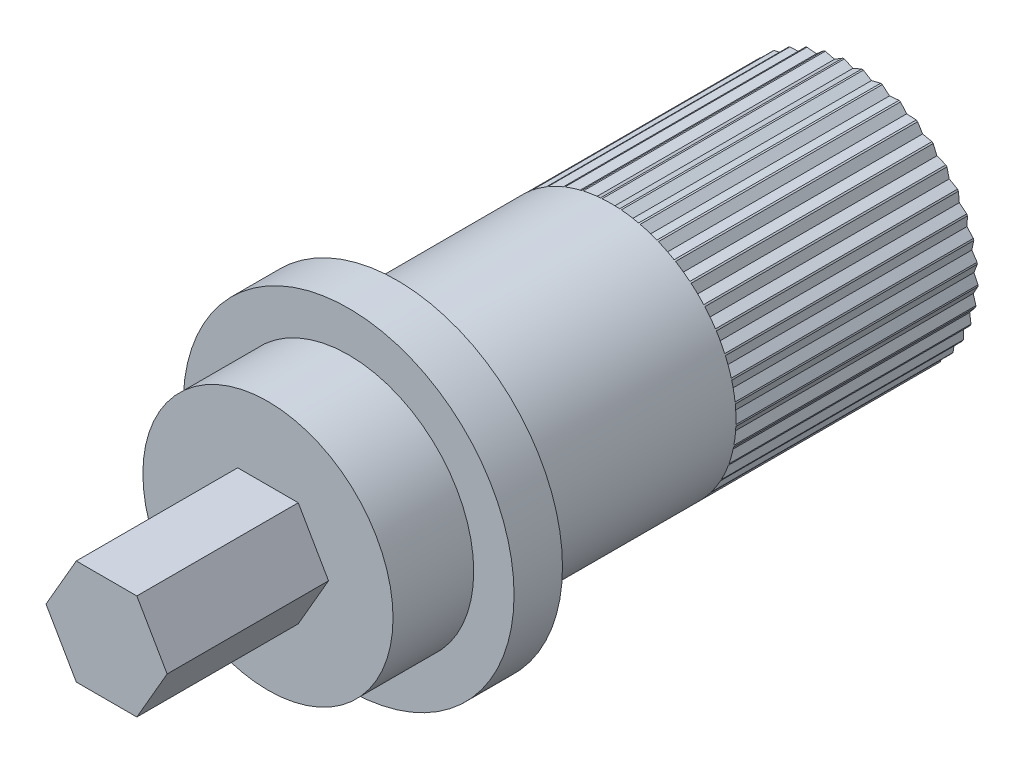
SolidWorks part; units mm, degrees
material "Nylon 101"
ref_plane "Front" through (0, 0, 0) normal (0, 0, 1) x (1, 0, 0)
ref_plane "Top" through (0, 0, 0) normal (0, 1, 0) x (1, 0, 0)
ref_plane "Right" through (0, 0, 0) normal (1, 0, 0) x (0, 0, -1)
sketch "Sketch1" plane through (0, 0, 0) normal (0, 0, 1) x (1, 0, 0)
  line L1 (1.5011, 0) -> (0.7506, 1.3)
  line L2 (0.7506, 1.3) -> (-0.7506, 1.3)
  line L3 (-0.7506, 1.3) -> (-1.5011, 0)
  line L4 (-1.5011, 0) -> (-0.7506, -1.3)
  line L5 (-0.7506, -1.3) -> (0.7506, -1.3)
  line L6 (0.7506, -1.3) -> (1.5011, 0)
  circle A0 centre (0, 0) radius 1.3 construction
  dimension "D1" = 2.6
extrude "Boss-Extrude1_ShaftHex" add sketch "Sketch1" along normal mid plane 4
sketch "Sketch2" plane through (0, 0, 0) normal (0, 0, 1) x (1, 0, 0)
  circle A0 centre (0, 0) radius 3.1
  dimension "D1" = 6.2
extrude "Boss-Extrude2_ShaftStop" add sketch "Sketch2" against normal blind 2 from surface at -2 starting at face at (0, 0, -2)
sketch "Sketch3" plane through (0, 0, 0) normal (0, 0, 1) x (1, 0, 0)
  circle A0 centre (0, 0) radius 4.1
  dimension "D1" = 8.2
extrude "Boss-Extrude3_ShaftBrim" add sketch "Sketch3" against normal blind 1.2 from surface at -4 starting at face at (3.1, 0, -4)
sketch "Sketch4" plane through (0, 0, 0) normal (0, 0, 1) x (1, 0, 0)
  circle A0 centre (0, 0) radius 3.1
  dimension "D1" = 6.2
extrude "Boss-Extrude4_ShaftKnob" add sketch "Sketch4" against normal blind 11.3 from surface at -5.2 starting at face at (4.1, 0, -5.2)
sketch "Sketch5" plane through (0, 0, 0) normal (0, 0, 1) x (1, 0, 0)
  line L0 (0.85, 0) -> (-0.85, 0)
  line L1 (0.35, 2.5) -> (-0.35, 2.5)
  line L2 (0.35, 2.5) -> (0.35, -2.5)
  line L3 (0.35, -2.5) -> (-0.35, -2.5)
  line L4 (-0.35, 2.5) -> (-0.35, -2.5)
  line L5 (0.35, 2.5) -> (-0.35, -2.5) construction
  line L6 (0.35, -2.5) -> (-0.35, 2.5) construction
  line L7 (-0.85, 0) -> (0, -1.4)
  line L8 (0, -1.4) -> (0.85, 0)
  point P0 (0, 0)
  point P8 (0, 0)
  point P10 (0, 0)
  dimension "D1" = 5
  dimension "D2" = 0.7
  dimension "D3" = 1.4
  dimension "D4" = 1.7
extrude "Cut-Extrude1_ShaftArrow" cut sketch "Sketch5" along normal blind 0.8 from surface at -16.5 contours L1 L4 L0 L2 | L0 L7 L4 | L7 L8 L2 L0 L4 | L2 L8 L0 | L8 L7 L4 L3 L2 starting at face at (3.1, 0, -16.5)
sketch "Sketch8" plane through (0, 0, 0) normal (0, 0, 1) x (1, 0, 0)
  line L0 (0.35, 2.5) -> (-0.35, 2.5) construction
  line L1 (0, 3.1) -> (0.235, 3.1)
  line L2 (0, 3.1) -> (-0.235, 3.1)
  line L3 (0.235, 3.1) -> (0, 3)
  line L4 (0, 3) -> (-0.235, 3.1)
  line L5 (0.235, 3.1) -> (0, 3.2513)
  line L6 (0, 3.2513) -> (-0.235, 3.1)
  line L7 (0.4732, 3.0637) -> (0.7055, 3.0278)
  line L8 (0.7055, 3.0278) -> (0.4579, 2.9648)
  line L9 (0.4579, 2.9648) -> (0.241, 3.0995)
  line L10 (0.4732, 3.0637) -> (0.241, 3.0995)
  line L11 (0.4963, 3.2132) -> (0.241, 3.0995)
  line L12 (0.7055, 3.0278) -> (0.4963, 3.2132)
  line L13 (0.9353, 2.9555) -> (1.1594, 2.8846)
  line L14 (1.1594, 2.8846) -> (0.9052, 2.8602)
  line L15 (0.9052, 2.8602) -> (0.7113, 3.0264)
  line L16 (0.9353, 2.9555) -> (0.7113, 3.0264)
  line L17 (0.981, 3.0998) -> (0.7113, 3.0264)
  line L18 (1.1594, 2.8846) -> (0.981, 3.0998)
  line L19 (1.3755, 2.7781) -> (1.5861, 2.6738)
  line L20 (1.5861, 2.6738) -> (1.3312, 2.6885)
  line L21 (1.3312, 2.6885) -> (1.1649, 2.8824)
  line L22 (1.3755, 2.7781) -> (1.1649, 2.8824)
  line L23 (1.4427, 2.9137) -> (1.1649, 2.8824)
  line L24 (1.5861, 2.6738) -> (1.4427, 2.9137)
  line L25 (1.7835, 2.5356) -> (1.9757, 2.4004)
  line L26 (1.9757, 2.4004) -> (1.726, 2.4538)
  line L27 (1.726, 2.4538) -> (1.5913, 2.6708)
  line L28 (1.7835, 2.5356) -> (1.5913, 2.6708)
  line L29 (1.8705, 2.6593) -> (1.5913, 2.6708)
  line L30 (1.9757, 2.4004) -> (1.8705, 2.6593)
  line L31 (2.1496, 2.2336) -> (2.319, 2.0707)
  line L32 (2.319, 2.0707) -> (2.0803, 2.1616)
  line L33 (2.0803, 2.1616) -> (1.9803, 2.3966)
  line L34 (2.1496, 2.2336) -> (1.9803, 2.3966)
  line L35 (2.2545, 2.3426) -> (1.9803, 2.3966)
  line L36 (2.319, 2.0707) -> (2.2545, 2.3426)
  line L37 (2.4654, 1.8793) -> (2.6079, 1.6924)
  line L38 (2.6079, 1.6924) -> (2.3859, 1.8187)
  line L39 (2.3859, 1.8187) -> (2.3229, 2.0662)
  line L40 (2.4654, 1.8793) -> (2.3229, 2.0662)
  line L41 (2.5857, 1.971) -> (2.3229, 2.0662)
  line L42 (2.6079, 1.6924) -> (2.5857, 1.971)
  line L43 (2.7234, 1.4809) -> (2.8357, 1.2745)
  line L44 (2.8357, 1.2745) -> (2.6355, 1.4332)
  line L45 (2.6355, 1.4332) -> (2.6111, 1.6874)
  line L46 (2.7234, 1.4809) -> (2.6111, 1.6874)
  line L47 (2.8563, 1.5532) -> (2.6111, 1.6874)
  line L48 (2.8357, 1.2745) -> (2.8563, 1.5532)
  line L49 (2.9175, 1.0479) -> (2.997, 0.8267)
  line L50 (2.997, 0.8267) -> (2.8234, 1.0141)
  line L51 (2.8234, 1.0141) -> (2.8381, 1.269)
  line L52 (2.9175, 1.0479) -> (2.8381, 1.269)
  line L53 (3.0599, 1.099) -> (2.8381, 1.269)
  line L54 (2.997, 0.8267) -> (3.0599, 1.099)
  line L55 (3.0433, 0.5902) -> (3.088, 0.3595)
  line L56 (3.088, 0.3595) -> (2.9451, 0.5712)
  line L57 (2.9451, 0.5712) -> (2.9986, 0.8209)
  line L58 (3.0433, 0.5902) -> (2.9986, 0.8209)
  line L59 (3.1918, 0.619) -> (2.9986, 0.8209)
  line L60 (3.088, 0.3595) -> (3.1918, 0.619)
  line L61 (3.0977, 0.1187) -> (3.1067, -0.1161)
  line L62 (3.1067, -0.1161) -> (2.9978, 0.1149)
  line L63 (2.9978, 0.1149) -> (3.0887, 0.3536)
  line L64 (3.0977, 0.1187) -> (3.0887, 0.3536)
  line L65 (3.2489, 0.1245) -> (3.0887, 0.3536)
  line L66 (3.1067, -0.1161) -> (3.2489, 0.1245)
  line L67 (3.0795, -0.3555) -> (3.0526, -0.589)
  line L68 (3.0526, -0.589) -> (2.9802, -0.3441)
  line L69 (2.9802, -0.3441) -> (3.1065, -0.1221)
  line L70 (3.0795, -0.3555) -> (3.1065, -0.1221)
  line L71 (3.2298, -0.3729) -> (3.1065, -0.1221)
  line L72 (3.0526, -0.589) -> (3.2298, -0.3729)
  line L73 (2.9892, -0.8214) -> (2.9269, -1.048)
  line L74 (2.9269, -1.048) -> (2.8928, -0.7949)
  line L75 (2.8928, -0.7949) -> (3.0515, -0.5948)
  line L76 (2.9892, -0.8214) -> (3.0515, -0.5948)
  line L77 (3.1351, -0.8615) -> (3.0515, -0.5948)
  line L78 (2.9269, -1.048) -> (3.1351, -0.8615)
  line L79 (2.8288, -1.2681) -> (2.7326, -1.4826)
  line L80 (2.7326, -1.4826) -> (2.7375, -1.2272)
  line L81 (2.7375, -1.2272) -> (2.9249, -1.0537)
  line L82 (2.8288, -1.2681) -> (2.9249, -1.0537)
  line L83 (2.9668, -1.33) -> (2.9249, -1.0537)
  line L84 (2.7326, -1.4826) -> (2.9668, -1.33)
  line L85 (2.602, -1.6851) -> (2.4743, -1.8823)
  line L86 (2.4743, -1.8823) -> (2.5181, -1.6307)
  line L87 (2.5181, -1.6307) -> (2.7298, -1.4878)
  line L88 (2.602, -1.6851) -> (2.7298, -1.4878)
  line L89 (2.729, -1.7673) -> (2.7298, -1.4878)
  line L90 (2.4743, -1.8823) -> (2.729, -1.7673)
  line L91 (2.3143, -2.0625) -> (2.158, -2.2379)
  line L92 (2.158, -2.2379) -> (2.2397, -1.996)
  line L93 (2.2397, -1.996) -> (2.4707, -1.8871)
  line L94 (2.3143, -2.0625) -> (2.4707, -1.8871)
  line L95 (2.4273, -2.1632) -> (2.4707, -1.8871)
  line L96 (2.158, -2.2379) -> (2.4273, -2.1632)
  line L97 (1.9724, -2.3916) -> (1.7911, -2.5411)
  line L98 (1.7911, -2.5411) -> (1.9087, -2.3145)
  line L99 (1.9087, -2.3145) -> (2.1537, -2.2421)
  line L100 (1.9724, -2.3916) -> (2.1537, -2.2421)
  line L101 (2.0686, -2.5083) -> (2.1537, -2.2421)
  line L102 (1.7911, -2.5411) -> (2.0686, -2.5083)
  line L103 (1.5842, -2.6647) -> (1.3822, -2.7848)
  line L104 (1.3822, -2.7848) -> (1.5331, -2.5787)
  line L105 (1.5331, -2.5787) -> (1.7862, -2.5446)
  line L106 (1.5842, -2.6647) -> (1.7862, -2.5446)
  line L107 (1.6615, -2.7947) -> (1.7862, -2.5446)
  line L108 (1.3822, -2.7848) -> (1.6615, -2.7947)
  line L109 (1.1588, -2.8753) -> (0.9409, -2.9631)
  line L110 (0.9409, -2.9631) -> (1.1215, -2.7825)
  line L111 (1.1215, -2.7825) -> (1.3768, -2.7874)
  line L112 (1.1588, -2.8753) -> (1.3768, -2.7874)
  line L113 (1.2154, -3.0156) -> (1.3768, -2.7874)
  line L114 (0.9409, -2.9631) -> (1.2154, -3.0156)
  line L115 (0.7063, -3.0185) -> (0.4775, -3.072)
  line L116 (0.4775, -3.072) -> (0.6836, -2.9211)
  line L117 (0.6836, -2.9211) -> (0.9352, -2.9649)
  line L118 (0.7063, -3.0185) -> (0.9352, -2.9649)
  line L119 (0.7408, -3.1658) -> (0.9352, -2.9649)
  line L120 (0.4775, -3.072) -> (0.7408, -3.1658)
  line L121 (0.2373, -3.0909) -> (0.003, -3.1089)
  line L122 (0.003, -3.1089) -> (0.2296, -2.9912)
  line L123 (0.2296, -2.9912) -> (0.4716, -3.0729)
  line L124 (0.2373, -3.0909) -> (0.4716, -3.0729)
  line L125 (0.2489, -3.2417) -> (0.4716, -3.0729)
  line L126 (0.003, -3.1089) -> (0.2489, -3.2417)
  line L127 (-0.2373, -3.0909) -> (-0.4716, -3.0729)
  line L128 (-0.4716, -3.0729) -> (-0.2296, -2.9912)
  line L129 (-0.2296, -2.9912) -> (-0.003, -3.1089)
  line L130 (-0.2373, -3.0909) -> (-0.003, -3.1089)
  line L131 (-0.2489, -3.2417) -> (-0.003, -3.1089)
  line L132 (-0.4716, -3.0729) -> (-0.2489, -3.2417)
  line L133 (-0.7063, -3.0185) -> (-0.9352, -2.9649)
  line L134 (-0.9352, -2.9649) -> (-0.6836, -2.9211)
  line L135 (-0.6836, -2.9211) -> (-0.4775, -3.072)
  line L136 (-0.7063, -3.0185) -> (-0.4775, -3.072)
  line L137 (-0.7408, -3.1658) -> (-0.4775, -3.072)
  line L138 (-0.9352, -2.9649) -> (-0.7408, -3.1658)
  line L139 (-1.1588, -2.8753) -> (-1.3768, -2.7874)
  line L140 (-1.3768, -2.7874) -> (-1.1215, -2.7825)
  line L141 (-1.1215, -2.7825) -> (-0.9409, -2.9631)
  line L142 (-1.1588, -2.8753) -> (-0.9409, -2.9631)
  line L143 (-1.2154, -3.0156) -> (-0.9409, -2.9631)
  line L144 (-1.3768, -2.7874) -> (-1.2154, -3.0156)
  line L145 (-1.5842, -2.6647) -> (-1.7862, -2.5446)
  line L146 (-1.7862, -2.5446) -> (-1.5331, -2.5787)
  line L147 (-1.5331, -2.5787) -> (-1.3822, -2.7848)
  line L148 (-1.5842, -2.6647) -> (-1.3822, -2.7848)
  line L149 (-1.6615, -2.7947) -> (-1.3822, -2.7848)
  line L150 (-1.7862, -2.5446) -> (-1.6615, -2.7947)
  line L151 (-1.9724, -2.3916) -> (-2.1537, -2.2421)
  line L152 (-2.1537, -2.2421) -> (-1.9087, -2.3145)
  line L153 (-1.9087, -2.3145) -> (-1.7911, -2.5411)
  line L154 (-1.9724, -2.3916) -> (-1.7911, -2.5411)
  line L155 (-2.0686, -2.5083) -> (-1.7911, -2.5411)
  line L156 (-2.1537, -2.2421) -> (-2.0686, -2.5083)
  line L157 (-2.3143, -2.0625) -> (-2.4707, -1.8871)
  line L158 (-2.4707, -1.8871) -> (-2.2397, -1.996)
  line L159 (-2.2397, -1.996) -> (-2.158, -2.2379)
  line L160 (-2.3143, -2.0625) -> (-2.158, -2.2379)
  line L161 (-2.4273, -2.1632) -> (-2.158, -2.2379)
  line L162 (-2.4707, -1.8871) -> (-2.4273, -2.1632)
  line L163 (-2.602, -1.6851) -> (-2.7298, -1.4878)
  line L164 (-2.7298, -1.4878) -> (-2.5181, -1.6307)
  line L165 (-2.5181, -1.6307) -> (-2.4743, -1.8823)
  line L166 (-2.602, -1.6851) -> (-2.4743, -1.8823)
  line L167 (-2.729, -1.7673) -> (-2.4743, -1.8823)
  line L168 (-2.7298, -1.4878) -> (-2.729, -1.7673)
  line L169 (-2.8288, -1.2681) -> (-2.9249, -1.0537)
  line L170 (-2.9249, -1.0537) -> (-2.7375, -1.2272)
  line L171 (-2.7375, -1.2272) -> (-2.7326, -1.4826)
  line L172 (-2.8288, -1.2681) -> (-2.7326, -1.4826)
  line L173 (-2.9668, -1.33) -> (-2.7326, -1.4826)
  line L174 (-2.9249, -1.0537) -> (-2.9668, -1.33)
  line L175 (-2.9892, -0.8214) -> (-3.0515, -0.5948)
  line L176 (-3.0515, -0.5948) -> (-2.8928, -0.7949)
  line L177 (-2.8928, -0.7949) -> (-2.9269, -1.048)
  line L178 (-2.9892, -0.8214) -> (-2.9269, -1.048)
  line L179 (-3.1351, -0.8615) -> (-2.9269, -1.048)
  line L180 (-3.0515, -0.5948) -> (-3.1351, -0.8615)
  line L181 (-3.0795, -0.3555) -> (-3.1065, -0.1221)
  line L182 (-3.1065, -0.1221) -> (-2.9802, -0.3441)
  line L183 (-2.9802, -0.3441) -> (-3.0526, -0.589)
  line L184 (-3.0795, -0.3555) -> (-3.0526, -0.589)
  line L185 (-3.2298, -0.3729) -> (-3.0526, -0.589)
  line L186 (-3.1065, -0.1221) -> (-3.2298, -0.3729)
  line L187 (-3.0977, 0.1187) -> (-3.0887, 0.3536)
  line L188 (-3.0887, 0.3536) -> (-2.9978, 0.1149)
  line L189 (-2.9978, 0.1149) -> (-3.1067, -0.1161)
  line L190 (-3.0977, 0.1187) -> (-3.1067, -0.1161)
  line L191 (-3.2489, 0.1245) -> (-3.1067, -0.1161)
  line L192 (-3.0887, 0.3536) -> (-3.2489, 0.1245)
  line L193 (-3.0433, 0.5902) -> (-2.9986, 0.8209)
  line L194 (-2.9986, 0.8209) -> (-2.9451, 0.5712)
  line L195 (-2.9451, 0.5712) -> (-3.088, 0.3595)
  line L196 (-3.0433, 0.5902) -> (-3.088, 0.3595)
  line L197 (-3.1918, 0.619) -> (-3.088, 0.3595)
  line L198 (-2.9986, 0.8209) -> (-3.1918, 0.619)
  line L199 (-2.9175, 1.0479) -> (-2.8381, 1.269)
  line L200 (-2.8381, 1.269) -> (-2.8234, 1.0141)
  line L201 (-2.8234, 1.0141) -> (-2.997, 0.8267)
  line L202 (-2.9175, 1.0479) -> (-2.997, 0.8267)
  line L203 (-3.0599, 1.099) -> (-2.997, 0.8267)
  line L204 (-2.8381, 1.269) -> (-3.0599, 1.099)
  line L205 (-2.7234, 1.4809) -> (-2.6111, 1.6874)
  line L206 (-2.6111, 1.6874) -> (-2.6355, 1.4332)
  line L207 (-2.6355, 1.4332) -> (-2.8357, 1.2745)
  line L208 (-2.7234, 1.4809) -> (-2.8357, 1.2745)
  line L209 (-2.8563, 1.5532) -> (-2.8357, 1.2745)
  line L210 (-2.6111, 1.6874) -> (-2.8563, 1.5532)
  line L211 (-2.4654, 1.8793) -> (-2.3229, 2.0662)
  line L212 (-2.3229, 2.0662) -> (-2.3859, 1.8187)
  line L213 (-2.3859, 1.8187) -> (-2.6079, 1.6924)
  line L214 (-2.4654, 1.8793) -> (-2.6079, 1.6924)
  line L215 (-2.5857, 1.971) -> (-2.6079, 1.6924)
  line L216 (-2.3229, 2.0662) -> (-2.5857, 1.971)
  line L217 (-2.1496, 2.2336) -> (-1.9803, 2.3966)
  line L218 (-1.9803, 2.3966) -> (-2.0803, 2.1616)
  line L219 (-2.0803, 2.1616) -> (-2.319, 2.0707)
  line L220 (-2.1496, 2.2336) -> (-2.319, 2.0707)
  line L221 (-2.2545, 2.3426) -> (-2.319, 2.0707)
  line L222 (-1.9803, 2.3966) -> (-2.2545, 2.3426)
  line L223 (-1.7835, 2.5356) -> (-1.5913, 2.6708)
  line L224 (-1.5913, 2.6708) -> (-1.726, 2.4538)
  line L225 (-1.726, 2.4538) -> (-1.9757, 2.4004)
  line L226 (-1.7835, 2.5356) -> (-1.9757, 2.4004)
  line L227 (-1.8705, 2.6593) -> (-1.9757, 2.4004)
  line L228 (-1.5913, 2.6708) -> (-1.8705, 2.6593)
  line L229 (-1.3755, 2.7781) -> (-1.1649, 2.8824)
  line L230 (-1.1649, 2.8824) -> (-1.3312, 2.6885)
  line L231 (-1.3312, 2.6885) -> (-1.5861, 2.6738)
  line L232 (-1.3755, 2.7781) -> (-1.5861, 2.6738)
  line L233 (-1.4427, 2.9137) -> (-1.5861, 2.6738)
  line L234 (-1.1649, 2.8824) -> (-1.4427, 2.9137)
  line L235 (-0.9353, 2.9555) -> (-0.7113, 3.0264)
  line L236 (-0.7113, 3.0264) -> (-0.9052, 2.8602)
  line L237 (-0.9052, 2.8602) -> (-1.1594, 2.8846)
  line L238 (-0.9353, 2.9555) -> (-1.1594, 2.8846)
  line L239 (-0.981, 3.0998) -> (-1.1594, 2.8846)
  line L240 (-0.7113, 3.0264) -> (-0.981, 3.0998)
  line L241 (-0.4732, 3.0637) -> (-0.241, 3.0995)
  line L242 (-0.241, 3.0995) -> (-0.4579, 2.9648)
  line L243 (-0.4579, 2.9648) -> (-0.7055, 3.0278)
  line L244 (-0.4732, 3.0637) -> (-0.7055, 3.0278)
  line L245 (-0.4963, 3.2132) -> (-0.7055, 3.0278)
  line L246 (-0.241, 3.0995) -> (-0.4963, 3.2132)
  point P13 (0, 2.5)
  dimension "D1" = 0.235
  dimension "D2" = 0.1
  dimension "D3" = 0.1513
  dimension "D4" = 0.5
  dimension "D5" = 41
extrude "Cut-Extrude3_KnobGrip" cut sketch "Sketch8" along normal blind 6 from surface at -16.5 contours L205 L208 L207 L206 | L205 L210 L209 L208 | L199 L202 L201 L200 | L199 L204 L203 L202 | L193 L198 L197 L196 | L187 L192 L191 L190 | L181 L186 L185 L184 | L181 L184 L183 L182 | L187 L190 L189 L188 | L193 L196 L195 L194 | L211 L214 L213 L212 | L211 L216 L215 L214 | L217 L222 L221 L220 | L217 L220 L219 L218 | L223 L228 L227 L226 | L223 L226 L225 L224 | L229 L234 L233 L232 | L229 L232 L231 L230 | L235 L238 L237 L236 | L235 L240 L239 L238 | L169 L174 L173 L172 | L169 L172 L171 L170 | L175 L178 L177 L176 | L175 L180 L179 L178 | L163 L168 L167 L166 | L163 L166 L165 L164 | L157 L160 L159 L158 | L157 L162 L161 L160 | L241 L244 L243 L242 | L241 L246 L245 L244 | L4 L3 L1 L2 | L5 L6 L2 L1 | L7 L12 L11 L10 | L7 L10 L9 L8 | L13 L18 L17 L16 | L13 L16 L15 L14 | L19 L24 L23 L22 | L19 L22 L21 L20 | L25 L30 L29 L28 | L25 L28 L27 L26 | L31 L36 L35 L34 | L31 L34 L33 L32 | L37 L42 L41 L40 | L37 L40 L39 L38 | L43 L48 L47 L46 | L43 L46 L45 L44 | L49 L54 L53 L52 | L49 L52 L51 L50 | L55 L60 L59 L58 | L55 L58 L57 L56 | L61 L66 L65 L64 | L61 L64 L63 L62 | L67 L72 L71 L70 | L73 L78 L77 L76 | L79 L84 L83 L82 | L85 L90 L89 L88 | L85 L88 L87 L86 | L79 L82 L81 L80 | L73 L76 L75 L74 | L67 L70 L69 L68 | L97 L102 L101 L100 | L103 L108 L107 L106 | L109 L114 L113 L112 | L115 L120 L119 L118 | L121 L126 L125 L124 | L127 L132 L131 L130 | L127 L130 L129 L128 | L121 L124 L123 L122 | L109 L112 L111 L110 | L103 L106 L105 L104 | L91 L96 L95 L94 | L91 L94 L93 L92 | L97 L100 L99 L98 | L115 L118 L117 L116 | L133 L138 L137 L136 | L151 L154 L153 L152 | L145 L148 L147 L146 | L139 L142 L141 L140 | L133 L136 L135 L134 | L139 L144 L143 L142 | L145 L150 L149 L148 | L151 L156 L155 L154 starting at face at (0, -0.1647, -16.5)
sketch "Sketch9" plane through (0, 0, 0) normal (0, 0, 1) x (1, 0, 0)
  circle A0 centre (0, 0) radius 2.9552
extrude "Cut-Extrude4" cut sketch "Sketch9" along normal blind 0.05 from surface at -16.5 starting at face at (0, -0.1647, -16.5)
